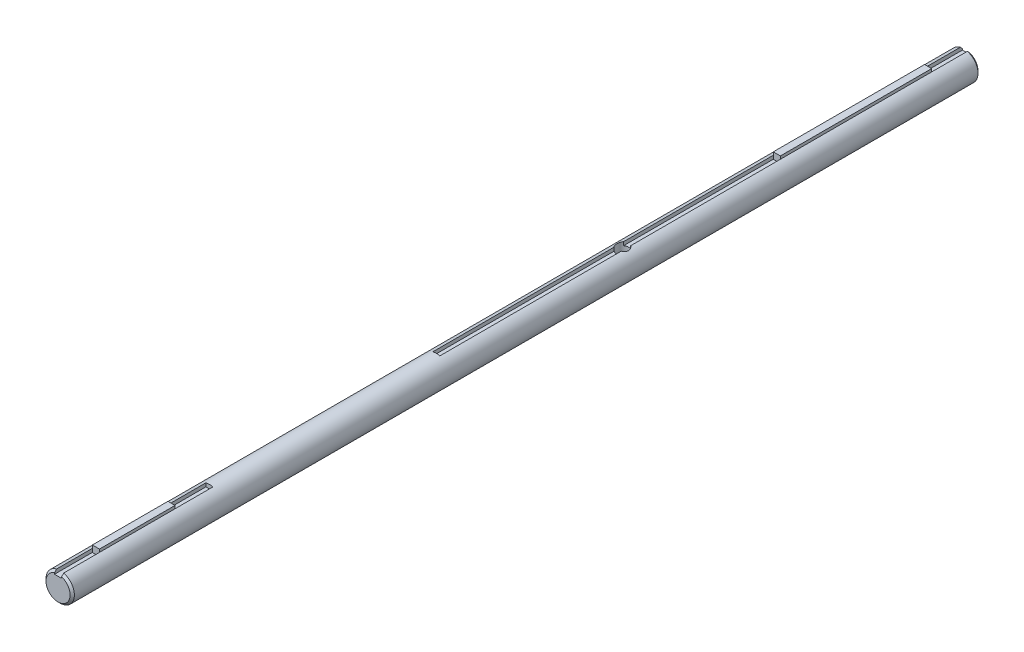
SolidWorks part; units mm, degrees
ref_plane "Front Plane" through (0, 0, 0) normal (0, 0, 1) x (1, 0, 0)
ref_plane "Top Plane" through (0, 0, 0) normal (0, 1, 0) x (1, 0, 0)
ref_plane "Right Plane" through (0, 0, 0) normal (1, 0, 0) x (0, 0, -1)
sketch "Sketch1" plane through (0, 0, 0) normal (0, 0, 1) x (1, 0, 0)
  line L0 (-2.3813, 6.8413) -> (2.3813, 6.8413)
  line L1 (-2.3813, 6.8413) -> (-2.3812, 9.2225)
  line L2 (2.3813, 6.8413) -> (2.3812, 9.2225)
  line L3 (-2.3812, 11.1792) -> (2.3812, 11.1792)
  line L4 (-2.3812, 11.1792) -> (-2.3812, 9.2225)
  line L5 (2.3812, 11.1792) -> (2.3812, 9.2225)
  circle A0 centre (0, 0) radius 9.525
  circle A1 centre (0, 0) radius 11.43 construction
  point P5 (0, 6.8413)
  point P11 (0, 9.525)
  dimension "Diameter" = 19.05
  dimension "D1" = 22.86
  dimension "Keyway Width" = 4.7625
  dimension "Keyway Depth" = 2.3813
  dimension "D2" = 4.7625
sketch "Sketch2" plane through (0, 0, 0) normal (1, 0, 0) x (0, 0, -1)
  line L0 (-304.8, 9.525) -> (304.8, 9.525)
  point P2 (-203.2, 9.525)
  point P3 (-50.8, 9.525)
  point P4 (-38.1, 9.525)
  point P5 (-279.4, 9.525)
  point P6 (-228.6, 9.525)
  point P7 (279.4, 9.525)
  point P8 (177.8, 9.525)
  point P9 (-171.45, 9.525)
  point P10 (171.45, 9.525)
  point P11 (-50.8, 9.525)
  point P12 (304.8, 9.525)
  point P13 (-63.5, 9.525)
  dimension "Length" = 609.6
  dimension "D1" = 25.4
  dimension "Key 1 Length" = 50.8
  dimension "D2" = 25.4
  dimension "Key 2 Length" = 101.6
  dimension "D3" = 133.35
  dimension "D4" = 133.35
  dimension "D5" = 12.7
  dimension "D6" = 12.7
sketch "Sketch3" plane through (0, 0, 0) normal (0, 0, 1) x (1, 0, 0)
  circle A0 centre (0, 0) radius 9.525 construction
  circle A1 centre (0, 0) radius 9.525
extrude "Boss-Extrude1" add sketch "Sketch3" along normal mid plane 609.6
chamfer "Chamfer1" distance 1.4287 angle 45 2 edges at (9.525, 0, -304.8) (9.525, 0, 304.8)
sketch "Sketch5" plane through (0, 0, 304.8) normal (0, 0, 1) x (1, 0, 0)
  line L0 (-2.3812, 11.1792) -> (2.3812, 11.1792) construction
  line L1 (2.3812, 11.1792) -> (2.3812, 9.2225) construction
  line L2 (2.3813, 6.8413) -> (2.3812, 9.2225) construction
  line L3 (-2.3813, 6.8413) -> (2.3813, 6.8413) construction
  line L4 (-2.3813, 6.8413) -> (-2.3812, 9.2225) construction
  line L5 (-2.3812, 11.1792) -> (-2.3812, 9.2225) construction
  line L6 (-2.3812, 11.1792) -> (2.3812, 11.1792)
  line L7 (2.3812, 11.1792) -> (2.3812, 9.2225)
  line L8 (2.3813, 6.8413) -> (2.3812, 9.2225)
  line L9 (-2.3813, 6.8413) -> (2.3813, 6.8413)
  line L10 (-2.3813, 6.8413) -> (-2.3812, 9.2225)
  line L11 (-2.3812, 11.1792) -> (-2.3812, 9.2225)
extrude "Cut-Extrude1" cut sketch "Sketch5" against normal up to vertex (609.6 mm away)
sketch "Sketch6" plane through (0, 0, -304.8) normal (0, 0, -1) x (-1, 0, 0)
  line L6 (2.3812, 11.1792) -> (-2.3812, 11.1792)
  line L7 (-2.3812, 11.1792) -> (-2.3812, 9.2225)
  line L8 (-2.3812, 9.2225) -> (-2.3813, 6.8413)
  line L9 (-2.3813, 6.8413) -> (2.3813, 6.8413)
  line L10 (2.3813, 6.8413) -> (2.3812, 9.2225)
  line L11 (2.3812, 9.2225) -> (2.3812, 11.1792)
  line L12 (2.3812, 11.1792) -> (-2.3812, 11.1792)
  line L13 (-2.3812, 11.1792) -> (-2.3812, 9.2225)
  line L14 (-2.3812, 9.2225) -> (-2.3813, 6.8413)
  line L15 (-2.3813, 6.8413) -> (2.3813, 6.8413)
  line L16 (2.3813, 6.8413) -> (2.3812, 9.2225)
  line L17 (2.3812, 9.2225) -> (2.3812, 11.1792)
  dimension "D1" = 0
extrude "Cut-Extrude2" cut sketch "Sketch6" against normal up to vertex (355.6 mm away) up to point (0, 9.525, 50.8)
ref_plane "Plane1" through (0, 0, 279.4) normal (0, 0, 1) x (1, 0, 0)
sketch "Sketch7" plane through (0, 0, 279.4) normal (0, 0, 1) x (1, 0, 0)
  line L0 (-2.3812, 11.1792) -> (-2.3812, 9.2225) construction
  line L1 (-2.3813, 6.8413) -> (-2.3812, 9.2225) construction
  line L2 (-2.3813, 6.8413) -> (2.3813, 6.8413) construction
  line L3 (2.3813, 6.8413) -> (2.3812, 9.2225) construction
  line L4 (2.3812, 11.1792) -> (2.3812, 9.2225) construction
  line L5 (-2.3812, 11.1792) -> (2.3812, 11.1792) construction
  line L6 (-2.3812, 11.1792) -> (-2.3812, 9.2225)
  line L7 (-2.3813, 6.8413) -> (-2.3812, 9.2225)
  line L8 (-2.3813, 6.8413) -> (2.3813, 6.8413)
  line L9 (2.3813, 6.8413) -> (2.3812, 9.2225)
  line L10 (2.3812, 11.1792) -> (2.3812, 9.2225)
  line L11 (-2.3812, 11.1792) -> (2.3812, 11.1792)
extrude "Boss-Extrude2" add sketch "Sketch7" against normal up to vertex (50.8 mm away) up to point (0, 9.525, 228.6)
ref_plane "Plane2" through (0, 0, -279.4) normal (0, 0, 1) x (1, 0, 0)
sketch "Sketch8" plane through (0, 0, -279.4) normal (0, 0, 1) x (1, 0, 0)
  line L0 (-2.3812, 11.1792) -> (-2.3812, 9.2225) construction
  line L1 (-2.3813, 6.8413) -> (-2.3812, 9.2225) construction
  line L2 (-2.3813, 6.8413) -> (2.3813, 6.8413) construction
  line L3 (2.3813, 6.8413) -> (2.3812, 9.2225) construction
  line L4 (2.3812, 11.1792) -> (2.3812, 9.2225) construction
  line L5 (-2.3812, 11.1792) -> (2.3812, 11.1792) construction
  line L6 (-2.3812, 11.1792) -> (-2.3812, 9.2225)
  line L7 (-2.3813, 6.8413) -> (-2.3812, 9.2225)
  line L8 (-2.3813, 6.8413) -> (2.3813, 6.8413)
  line L9 (2.3813, 6.8413) -> (2.3812, 9.2225)
  line L10 (2.3812, 11.1792) -> (2.3812, 9.2225)
  line L11 (-2.3812, 11.1792) -> (2.3812, 11.1792)
extrude "Boss-Extrude3" add sketch "Sketch8" along normal up to vertex (101.6 mm away) up to point (0, 9.525, -177.8)
sketch "Sketch9" plane through (0, 0, 0) normal (0, 1, 0) x (1, 0, 0)
  line L0 (2.3813, 304.8) -> (-2.3813, 304.8) construction
  line L1 (0, 74.168) -> (-9.525, 74.168) construction
  line L2 (-9.525, 303.3712) -> (-9.525, -303.3713) construction
  line L3 (0, 74.168) -> (9.525, 74.168) construction
  line L4 (9.525, -303.3713) -> (9.525, 303.3712) construction
  circle A1 centre (0, 74.168) radius 3.9687
  point P0 (0, 74.168)
  dimension "D2" = 7.9375
  dimension "D1" = 230.632
extrude "Cut-Extrude3" cut sketch "Sketch9" against normal through all both and the other way through all
equation "\"D1@Sketch1\"=\"Diameter@Sketch1\"*1.2"
equation "\"D1@Boss-Extrude1\"=\"length@sketch2\""
equation "\"D1@Chamfer1\"=\"Diameter@Sketch1\"*0.075"
equation "\"D4@Sketch2\"=\"D3@Sketch2\""
equation "\"D6@Sketch2\"=\"D5@Sketch2\""
